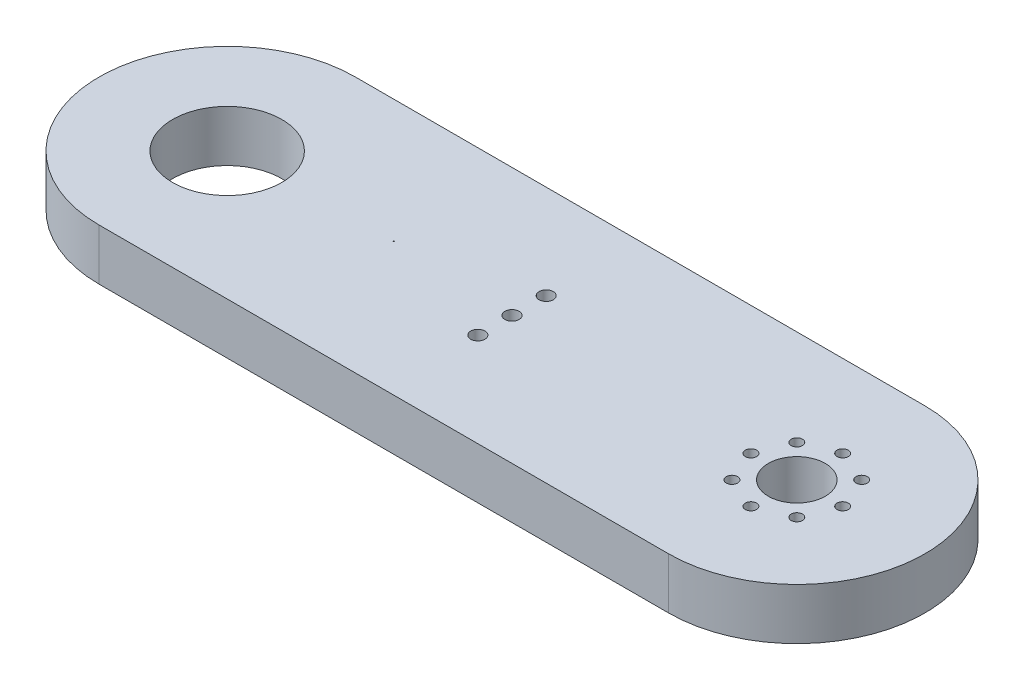
SolidWorks part; units mm, degrees
ref_plane "Front Plane" through (0, 0, 0) normal (0, 0, 1) x (1, 0, 0)
ref_plane "Top Plane" through (0, 0, 0) normal (0, 1, 0) x (1, 0, 0)
ref_plane "Right Plane" through (0, 0, 0) normal (1, 0, 0) x (0, 0, -1)
sketch "Sketch2" plane through (0, 0, 0) normal (0, 1, 0) x (1, 0, 0)
  line L0 (50, 0) -> (-50, 0) construction
  line L1 (50, -22.5) -> (-50, -22.5)
  line L2 (50, 22.5) -> (-50, 22.5)
  arc A0 (50, -22.5) -> (50, 22.5) centre (50, 0) ccw
  arc A1 (-50, 22.5) -> (-50, -22.5) centre (-50, 0) ccw
  point P2 (0, 0)
  dimension "D2" = 100
  dimension "D1" = 45
extrude "Boss-Extrude1" add sketch "Sketch2" along normal mid plane 9
sketch "Sketch3" plane through (0, 4.5, 0) normal (0, 1, 0) x (1, 0, 0)
  circle A1 centre (50, 0) radius 1.9176 construction
  arc A2 (50, -22.5) -> (50, 22.5) centre (50, 0) ccw construction
  circle A3 centre (41.95, 0) radius 0.99
  circle A17 centre (44.3078, 5.6922) radius 0.99
  circle A18 centre (50, 8.05) radius 0.99
  circle A19 centre (55.6922, 5.6922) radius 0.99
  circle A20 centre (58.05, 0) radius 0.99
  circle A21 centre (55.6922, -5.6922) radius 0.99
  circle A22 centre (50, -8.05) radius 0.99
  circle A23 centre (44.3078, -5.6922) radius 0.99
  dimension "D2" = 1.98
  dimension "D4" = 20.5824
  dimension "D1" = 8.05
  dimension "D3" = 8
extrude "Cut-Extrude1" cut sketch "Sketch3" against normal through all both and the other way through all
sketch "Sketch4" plane through (0, 4.5, 0) normal (0, 1, 0) x (1, 0, 0)
  circle A0 centre (50, 0) radius 5
  arc A1 (50, -22.5) -> (50, 22.5) centre (50, 0) ccw construction
  dimension "D1" = 10
extrude "Cut-Extrude2" cut sketch "Sketch4" against normal through all
sketch "Sketch5" plane through (0, 4.5, 0) normal (0, 1, 0) x (1, 0, 0)
  circle A0 centre (0, 6) radius 1.25
  arc A5 (-50, 22.5) -> (-50, -22.5) centre (-50, 0) ccw construction
  circle A6 centre (0, 0) radius 1.25
  circle A7 centre (0, -6) radius 1.25
  dimension "D2" = 2.5
  dimension "D3" = 50
  dimension "D1" = 3
extrude "Cut-Extrude3" cut sketch "Sketch5" against normal through all both and the other way through all
sketch "Sketch6" plane through (0, 4.5, 0) normal (0, 1, 0) x (1, 0, 0)
  circle A0 centre (-50, 0) radius 9.5918
  arc A1 (-50, 22.5) -> (-50, -22.5) centre (-50, 0) ccw construction
extrude "Cut-Extrude4" cut sketch "Sketch6" against normal through all both and the other way through all contours A0
hole_wizard "#97 (0.0059) Diameter Hole1" positions "3DSketch1" profile "Sketch7" hole size "#97" standard "ANSI Inch"
sketch3d "3DSketch1"
  point P0 (-40.4233, 2.2893, 0.538)
  point P1 (-21.6659, -4.5, -0.9069)
sketch "Sketch7" plane through (-21.6659, -4.5, -0.9069) normal (1, 0, 0) x (0, 0, -1)
  line L0 (0, 0) -> (0, 9)
  line L1 (0, 9) -> (0.0749, 9)
  line L2 (0.0749, 9) -> (0.0749, 0)
  line L5 (0.0749, 0) -> (0, 0)
  line L11 (0, -6.35) -> (0, 107.95) construction
  dimension "Thru Hole Dia." = 0.1499
  dimension "Thru Hole Depth" = 9
